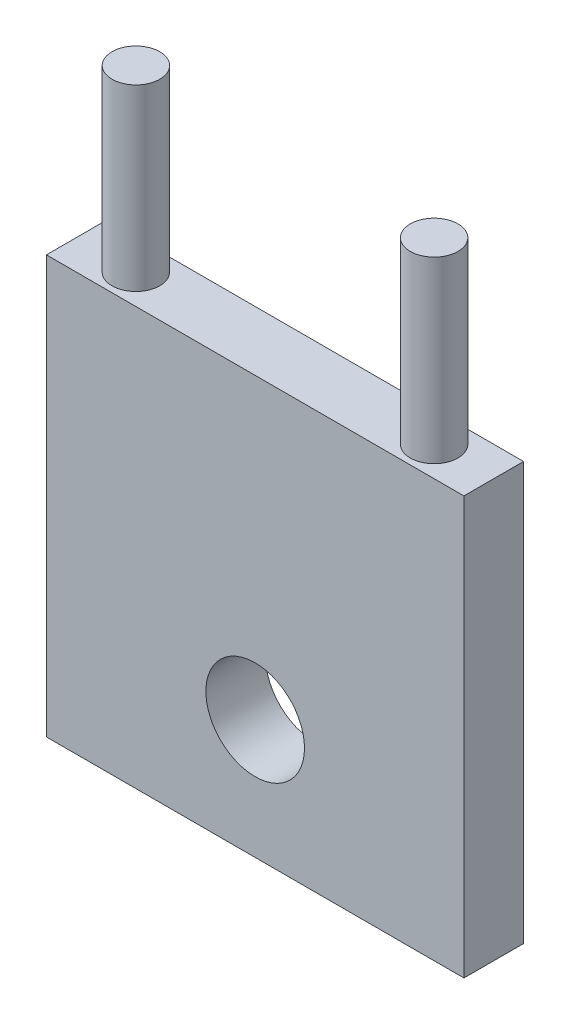
SolidWorks part; units mm, degrees
ref_plane "Front Plane" through (0, 0, 0) normal (0, 0, 1) x (1, 0, 0)
ref_plane "Top Plane" through (0, 0, 0) normal (0, 1, 0) x (1, 0, 0)
ref_plane "Right Plane" through (0, 0, 0) normal (1, 0, 0) x (0, 0, -1)
sketch "Sketch1" plane through (0, 0, 0) normal (0, 0, 1) x (1, 0, 0)
  line L0 (0, 0) -> (0, 17.78)
  line L1 (0, 17.78) -> (17.78, 17.78)
  line L2 (17.78, 17.78) -> (17.78, 0)
  line L3 (17.78, 0) -> (0, 0)
  circle A0 centre (8.89, 5.08) radius 2.1
  point P7 (8.89, 17.78)
  dimension "D3" = 4.2
  dimension "D1" = 17.78
  dimension "D2" = 17.78
  dimension "D4" = 5.08
extrude "Boss-Extrude1" add sketch "Sketch1" against normal blind 2.54
sketch "Sketch2" plane through (0, 17.78, 0) normal (0, 1, 0) x (1, 0, 0)
  line L0 (0, 2.54) -> (0, 0) construction
  circle A0 centre (2.54, 1.27) radius 1.016
  circle A1 centre (15.24, 1.27) radius 1.016
  point P7 (0, 1.27)
  dimension "D1" = 2.032
  dimension "D2" = 2.032
  dimension "D3" = 12.7
  dimension "D4" = 2.54
extrude "Boss-Extrude2" add sketch "Sketch2" along normal blind 7.62
